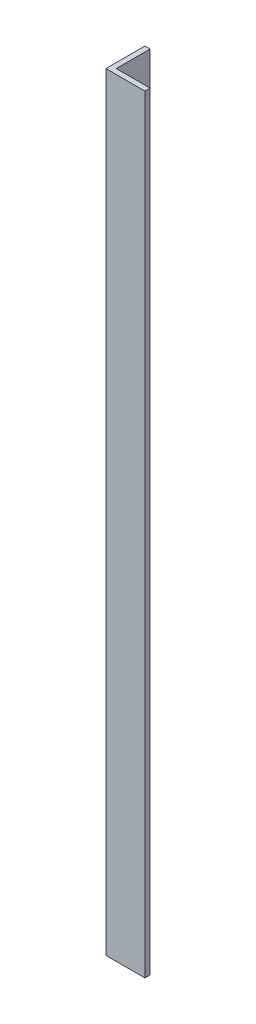
SolidWorks part; units mm, degrees
ref_plane "Ebene vorne" through (0, 0, 0) normal (0, 0, 1) x (1, 0, 0)
ref_plane "Ebene oben" through (0, 0, 0) normal (0, 1, 0) x (1, 0, 0)
ref_plane "Ebene rechts" through (0, 0, 0) normal (1, 0, 0) x (0, 0, -1)
sketch "Skizze1" plane through (0, 0, 0) normal (0, 1, 0) x (1, 0, 0)
  line L0 (0, 0) -> (15, 0)
  line L1 (15, 0) -> (15, 2)
  line L2 (15, 2) -> (2, 2)
  line L3 (2, 2) -> (2, 15)
  line L4 (2, 15) -> (0, 15)
  line L5 (0, 15) -> (0, 0)
  dimension "D1" = 15
  dimension "D2" = 2
extrude "Aufsatz-Linear austragen1" add sketch "Skizze1" along normal blind 295
